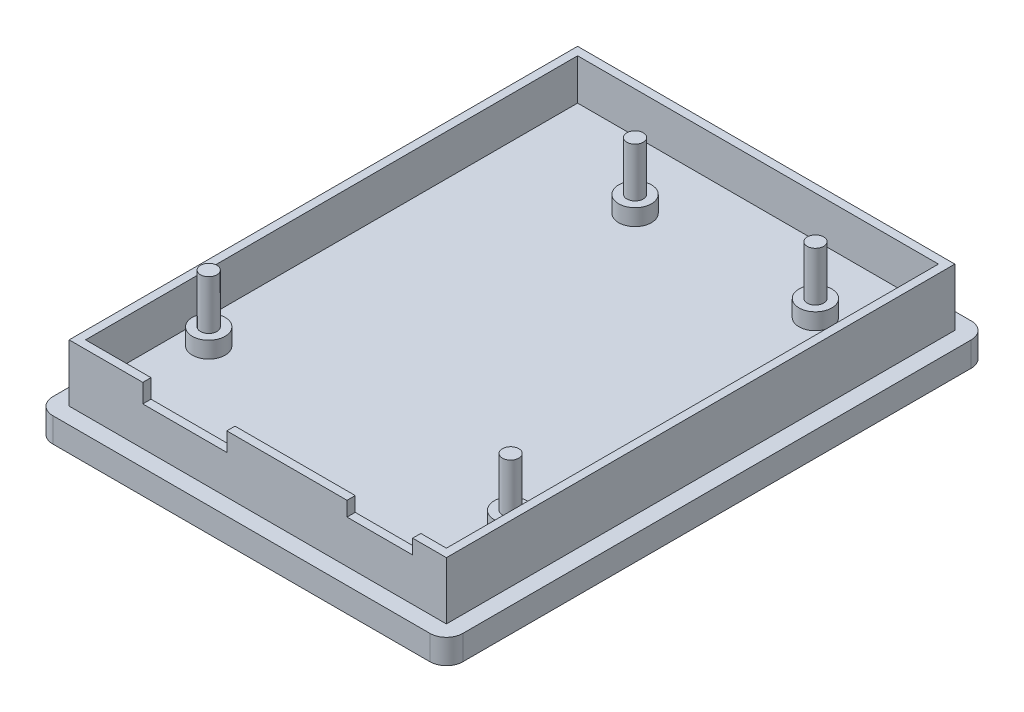
SolidWorks part; units mm, degrees
ref_plane "Front Plane" through (0, 0, 0) normal (0, 0, 1) x (1, 0, 0)
ref_plane "Top Plane" through (0, 0, 0) normal (0, 1, 0) x (1, 0, 0)
ref_plane "Right Plane" through (0, 0, 0) normal (1, 0, 0) x (0, 0, -1)
sketch "Sketch1" plane through (0, 0, 0) normal (0, 1, 0) x (1, 0, 0)
  line L1 (-31.75, 41.91) -> (31.75, 41.91)
  line L2 (-31.75, 41.91) -> (-31.75, -41.91)
  line L3 (-31.75, -41.91) -> (31.75, -41.91)
  line L4 (31.75, 41.91) -> (31.75, -41.91)
  line L5 (-31.75, 41.91) -> (31.75, -41.91) construction
  line L6 (-31.75, -41.91) -> (31.75, 41.91) construction
  point P0 (0, 0)
  dimension "D1" = 83.82
  dimension "D2" = 63.5
extrude "Boss-Extrude1" add sketch "Sketch1" along normal blind 12.7
sketch "Sketch2" plane through (0, 12.7, 0) normal (0, 1, 0) x (1, 0, 0)
  line L1 (27.94, -38.1) -> (-27.94, -38.1)
  line L2 (27.94, -38.1) -> (27.94, 38.1)
  line L3 (27.94, 38.1) -> (-27.94, 38.1)
  line L4 (-27.94, -38.1) -> (-27.94, 38.1)
  line L5 (27.94, -38.1) -> (-27.94, 38.1) construction
  line L6 (27.94, 38.1) -> (-27.94, -38.1) construction
  point P0 (0, 0)
  dimension "D1" = 55.88
  dimension "D2" = 76.2
extrude "Cut-Extrude1" cut sketch "Sketch2" against normal blind 6.35
sketch "Sketch3" plane through (0, 12.7, 0) normal (0, 1, 0) x (1, 0, 0)
  line L0 (29.21, -39.37) -> (29.21, 39.37)
  line L1 (31.75, -41.91) -> (-31.75, -41.91)
  line L2 (31.75, -41.91) -> (31.75, 41.91)
  line L3 (31.75, 41.91) -> (-31.75, 41.91)
  line L4 (-31.75, -41.91) -> (-31.75, 41.91)
  line L5 (29.21, 39.37) -> (-29.21, 39.37)
  line L6 (-29.21, -39.37) -> (-29.21, 39.37)
  line L7 (29.21, -39.37) -> (-29.21, -39.37)
  dimension "D1" = 2.54
extrude "Cut-Extrude2" cut sketch "Sketch3" against normal blind 8.89
sketch "Sketch6" plane through (0, 6.35, 0) normal (0, 1, 0) x (1, 0, 0)
  circle A0 centre (-23.9589, -23.0085) radius 1.27
  circle A1 centre (-8.7189, 27.7788) radius 1.27
  circle A2 centre (19.2084, 27.7788) radius 1.27
  circle A3 centre (24.0129, -24.2258) radius 1.27
  dimension "D1" = 2.54
  dimension "D2" = 2.54
  dimension "D3" = 2.54
  dimension "D4" = 2.54
extrude "Boss-Extrude3" add sketch "Sketch6" along normal blind 10.16
sketch "Sketch8" plane through (0, 6.35, 0) normal (0, 1, 0) x (1, 0, 0)
  circle A0 centre (19.2084, 27.7788) radius 2.54
  circle A1 centre (-8.7189, 27.7788) radius 2.54
  circle A2 centre (-23.9589, -23.0085) radius 2.54
  circle A3 centre (24.0129, -24.2258) radius 2.54
  dimension "D1" = 5.08
  dimension "D2" = 5.08
  dimension "D3" = 5.08
  dimension "D4" = 5.08
extrude "Boss-Extrude4" add sketch "Sketch8" along normal blind 2.54
sketch "Sketch10" plane through (0, 0, 39.37) normal (0, 0, 1) x (1, 0, 0)
  line L1 (-17.8088, 9.8083) -> (-4.7984, 9.8083)
  line L2 (-17.8088, 9.8083) -> (-17.8088, 13.1336)
  line L3 (-17.8088, 13.1336) -> (-4.7984, 13.1336)
  line L4 (-4.7984, 9.8083) -> (-4.7984, 13.1336)
extrude "Cut-Extrude4" cut sketch "Sketch10" against normal blind 10.16
sketch "Sketch11" plane through (0, 0, 39.37) normal (0, 0, 1) x (1, 0, 0)
  line L1 (23.9812, 10.4446) -> (13.8212, 10.4446)
  line L2 (23.9812, 10.4446) -> (23.9812, 13.0737)
  line L3 (23.9812, 13.0737) -> (13.8212, 13.0737)
  line L4 (13.8212, 10.4446) -> (13.8212, 13.0737)
extrude "Cut-Extrude5" cut sketch "Sketch11" against normal blind 10.16
fillet "Fillet1" radius 2.54 4 edges at (-31.75, 1.905, -41.91) (31.75, 1.905, -41.91) (-31.75, 1.905, 41.91) (31.75, 1.905, 41.91)
